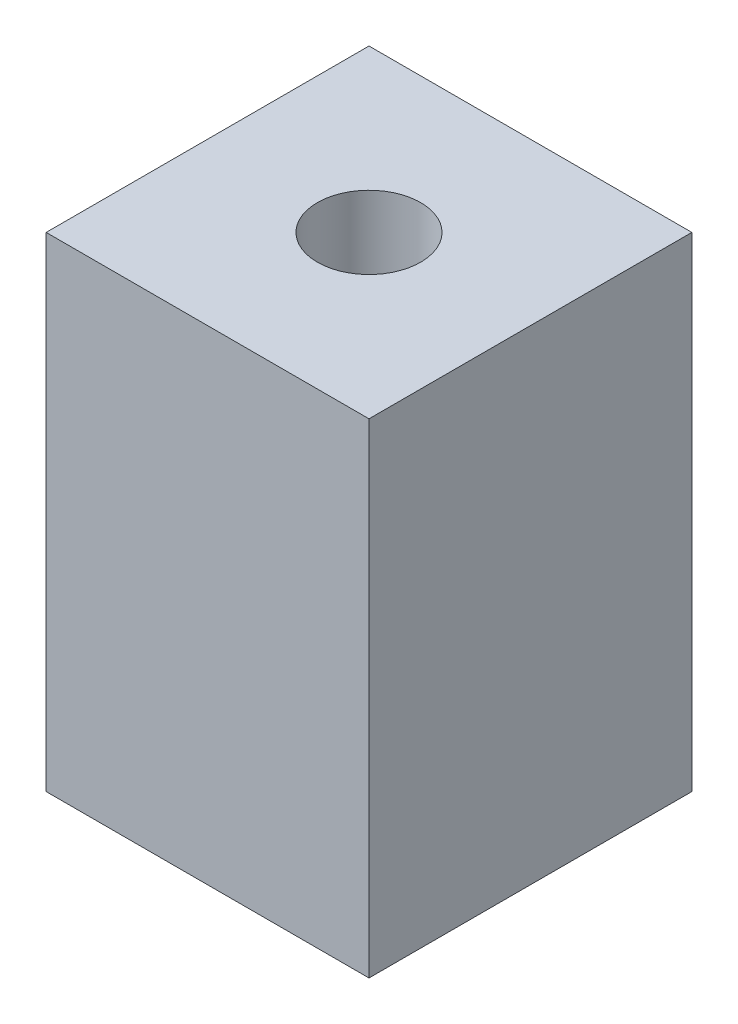
SolidWorks part; units mm, degrees
ref_plane "Front Plane" through (0, 0, 0) normal (0, 0, 1) x (1, 0, 0)
ref_plane "Top Plane" through (0, 0, 0) normal (0, 1, 0) x (1, 0, 0)
ref_plane "Right Plane" through (0, 0, 0) normal (1, 0, 0) x (0, 0, -1)
sketch "Sketch1" plane through (0, 0, 0) normal (0, 1, 0) x (1, 0, 0)
  line L1 (-20, 10) -> (0, 10)
  line L2 (-20, 10) -> (-20, -10)
  line L3 (-20, -10) -> (0, -10)
  line L4 (0, 10) -> (0, -10)
  dimension "D1" = 20
extrude "Boss-Extrude1" add sketch "Sketch1" along normal blind 30
sketch "Sketch2" plane through (0, 30, 0) normal (0, 1, 0) x (1, 0, 0)
  line L4 (-20, -10) -> (0, -10) construction
  circle A0 centre (-10, 0) radius 3.2
  point P2 (0, 0)
  point P3 (-9.6273, -2.5143)
  point P4 (0, 0)
  point P5 (0, 0)
  point P8 (-10, -10)
  dimension "D1" = 6.4
extrude "Cut-Extrude1" cut sketch "Sketch2" against normal through all
